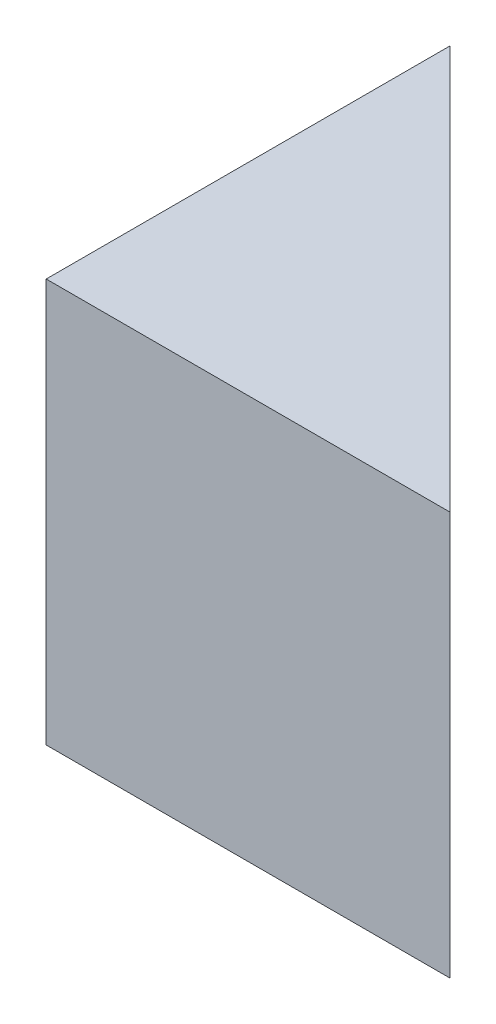
SolidWorks part; units mm, degrees
ref_plane "Front Plane" through (0, 0, 0) normal (0, 0, 1) x (1, 0, 0)
ref_plane "Top Plane" through (0, 0, 0) normal (0, 1, 0) x (1, 0, 0)
ref_plane "Right Plane" through (0, 0, 0) normal (1, 0, 0) x (0, 0, -1)
sketch "Sketch1" plane through (0, 0, 0) normal (0, 1, 0) x (1, 0, 0)
  line L0 (0, 0) -> (30, 0)
  line L1 (30, 0) -> (0, 30)
  line L2 (0, 30) -> (0, 0)
  dimension "D1" = 30
  dimension "D2" = 30
extrude "Boss-Extrude1" add sketch "Sketch1" along normal blind 30
